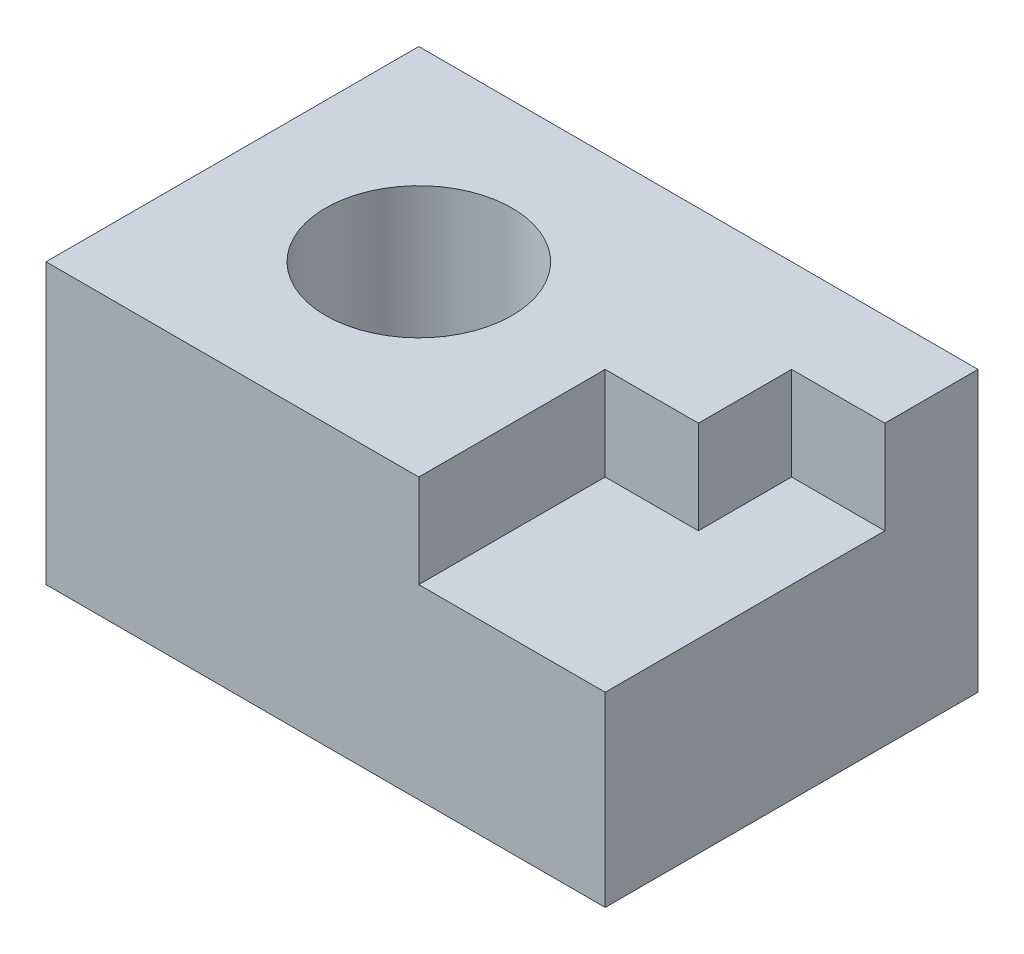
SolidWorks part; units mm, degrees
ref_plane "Front Plane" through (0, 0, 0) normal (0, 0, 1) x (1, 0, 0)
ref_plane "Top Plane" through (0, 0, 0) normal (0, 1, 0) x (1, 0, 0)
ref_plane "Right Plane" through (0, 0, 0) normal (1, 0, 0) x (0, 0, -1)
sketch "Sketch1" plane through (0, 0, 0) normal (0, 1, 0) x (1, 0, 0)
  line L1 (0, 0) -> (152.4, 0)
  line L2 (0, 0) -> (0, 101.6)
  line L3 (0, 101.6) -> (152.4, 101.6)
  line L4 (152.4, 0) -> (152.4, 101.6)
  dimension "D1" = 152.4
  dimension "D2" = 101.6
extrude "Boss-Extrude1" add sketch "Sketch1" along normal blind 76.2 contours L2 L3 L4 L1
sketch "Sketch2" plane through (0, 76.2, 0) normal (0, 1, 0) x (1, 0, 0)
  line L0 (0, 0) -> (152.4, 0) construction
  line L1 (152.4, 0) -> (152.4, 101.6) construction
  line L2 (101.6, 0) -> (152.4, 0)
  line L3 (152.4, 0) -> (152.4, 76.2)
  line L4 (152.4, 76.2) -> (127, 76.2)
  line L5 (127, 76.2) -> (127, 50.8)
  line L6 (127, 50.8) -> (101.6, 50.8)
  line L7 (101.6, 50.8) -> (101.6, 0)
  line L8 (0, 101.6) -> (152.4, 101.6) construction
  dimension "D1" = 25.4
  dimension "D2" = 25.4
  dimension "D3" = 25.4
  dimension "D4" = 25.4
extrude "Cut-Extrude1" cut sketch "Sketch2" against normal blind 25.4
sketch "Sketch3" plane through (0, 76.2, 0) normal (0, 1, 0) x (1, 0, 0)
  line L0 (0, 0) -> (0, 101.6) construction
  line L1 (0, 0) -> (0, 101.6) construction
  line L2 (0, 0) -> (101.6, 0) construction
  line L3 (0, 0) -> (101.6, 0) construction
  circle A0 centre (50.8, 50.8) radius 25.4
  dimension "D1" = 50.8
  dimension "D2" = 50.8
  dimension "D3" = 50.8
extrude "Cut-Extrude2" cut sketch "Sketch3" against normal through all
